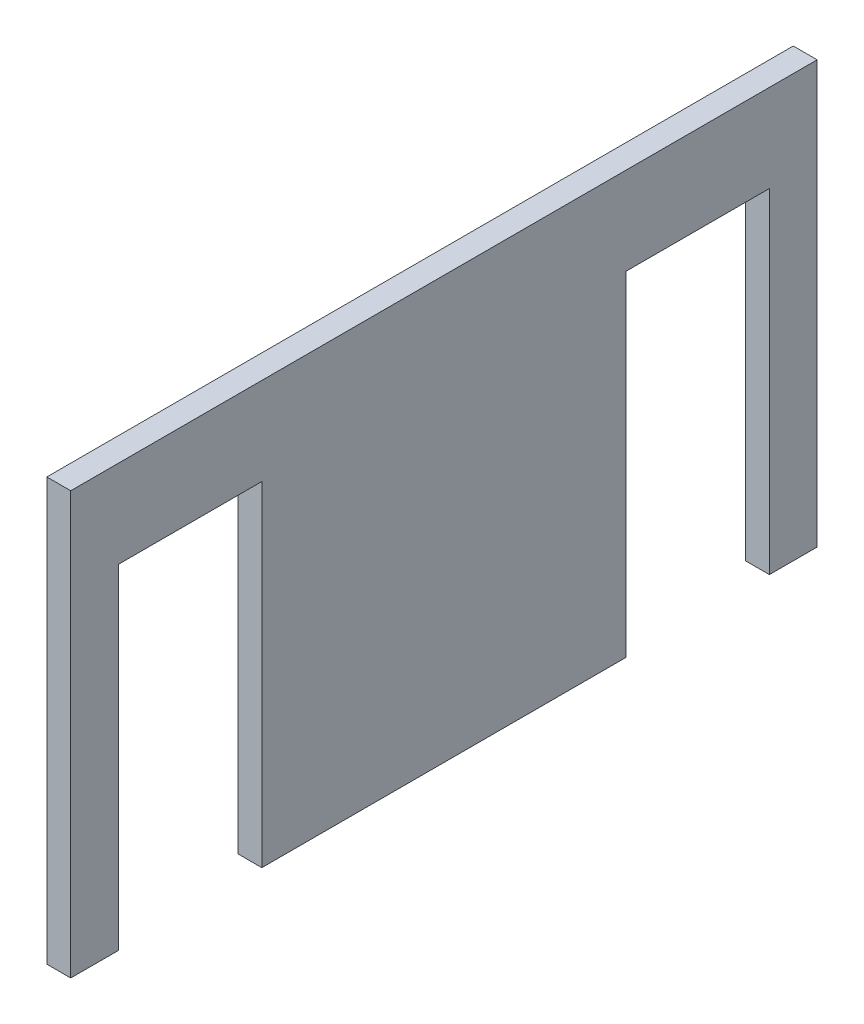
SolidWorks part; units mm, degrees
ref_plane "Front Plane" through (0, 0, 0) normal (0, 0, 1) x (1, 0, 0)
ref_plane "Top Plane" through (0, 0, 0) normal (0, 1, 0) x (1, 0, 0)
ref_plane "Right Plane" through (0, 0, 0) normal (1, 0, 0) x (0, 0, -1)
sketch "Sketch1" plane through (0, 0, 0) normal (0, 1, 0) x (1, 0, 0)
  line L1 (-76.2, -2381.25) -> (76.2, -2381.25)
  line L2 (-76.2, -2381.25) -> (-76.2, 2381.25)
  line L3 (-76.2, 2381.25) -> (76.2, 2381.25)
  line L4 (76.2, -2381.25) -> (76.2, 2381.25)
  line L5 (-76.2, -2381.25) -> (76.2, 2381.25) construction
  line L6 (-76.2, 2381.25) -> (76.2, -2381.25) construction
  point P0 (0, 0)
  dimension "D1" = 4762.5
  dimension "D2" = 152.4
extrude "Boss-Extrude1" add sketch "Sketch1" along normal blind 2692.4
sketch "Sketch2" plane through (76.2, 0, 0) normal (1, 0, 0) x (0, 0, -1)
  line L0 (-2381.25, 0) -> (2381.25, 0) construction
  line L1 (-2076.45, 2133.6) -> (-1162.05, 2133.6)
  line L2 (-2076.45, 2133.6) -> (-2076.45, 0)
  line L3 (-2076.45, 0) -> (-1162.05, 0)
  line L4 (-1162.05, 2133.6) -> (-1162.05, 0)
  line L5 (-2076.45, 2133.6) -> (-1162.05, 0) construction
  line L6 (-2076.45, 0) -> (-1162.05, 2133.6) construction
  line L7 (-2381.25, 2692.4) -> (-2381.25, 0) construction
  point P0 (-1619.25, 1066.8)
  dimension "D1" = 914.4
  dimension "D2" = 2133.6
  dimension "D3" = 304.8
extrude "Cut-Extrude1" cut sketch "Sketch2" against normal through all
mirror "Mirror1" about plane through (0, 0, 0) normal (0, 0, 1) of "Cut-Extrude1"
